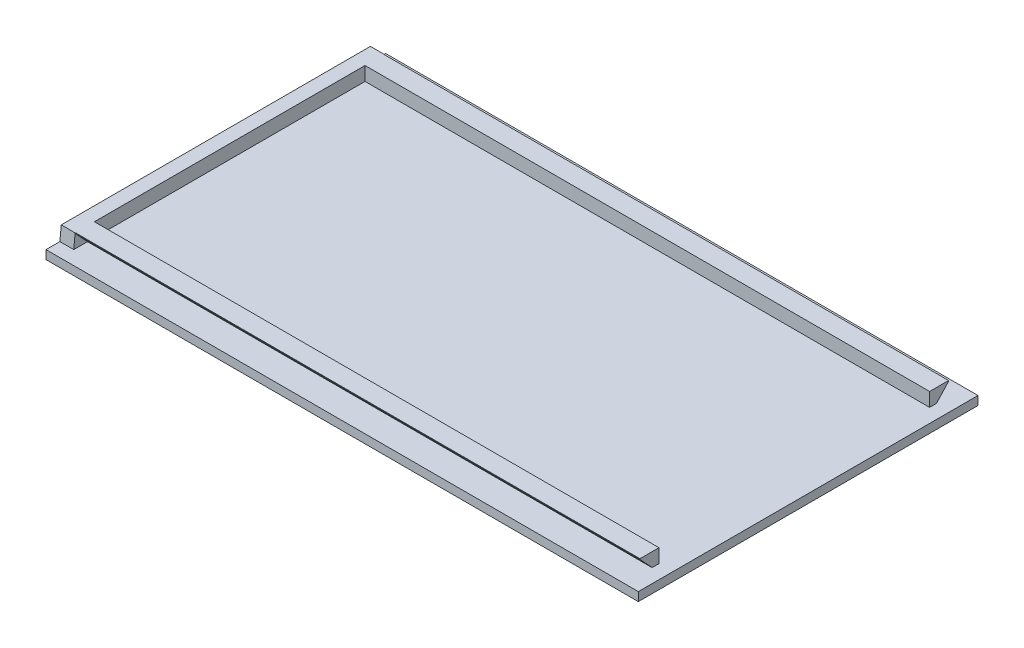
SolidWorks part; units mm, degrees
ref_plane "Plano frontal" through (0, 0, 0) normal (0, 0, 1) x (1, 0, 0)
ref_plane "Plano superior" through (0, 0, 0) normal (0, 1, 0) x (1, 0, 0)
ref_plane "Plano direito" through (0, 0, 0) normal (1, 0, 0) x (0, 0, -1)
sketch "Esboço1" plane through (0, 0, 0) normal (0, 1, 0) x (1, 0, 0)
  line L1 (0, 0) -> (85.8, 0)
  line L2 (0, 0) -> (0, 49.2)
  line L3 (0, 49.2) -> (85.8, 49.2)
  line L4 (85.8, 0) -> (85.8, 49.2)
  dimension "D1" = 85.8
  dimension "D2" = 49.2
extrude "Ressalto-extrusão1" add sketch "Esboço1" along normal blind 1.26
sketch "Esboço9" plane through (0, 0, 0) normal (-1, 0, 0) x (0, 0, 1)
  line L0 (-47.19, 1.26) -> (-46.9898, 3.26)
  line L1 (-49.2, 1.26) -> (0, 1.26) construction
  line L2 (-24.6, 1.26) -> (-24.6, 12.5039) construction
  line L3 (-46.9898, 3.26) -> (-2.2102, 3.26)
  line L4 (-2.01, 1.26) -> (-2.2102, 3.26)
  line L5 (-47.19, 1.26) -> (-2.01, 1.26)
  point P8 (-24.6, 3.26)
  dimension "D1" = 2
  dimension "D2" = 2.01
  dimension "D3" = 2.01
extrude "Ressalto-extrusão5" add sketch "Esboço9" against normal blind 2.01
sketch "Esboço11" plane through (85.8, 0, 0) normal (1, 0, 0) x (0, 0, -1)
  line L0 (44.2, 1.26) -> (45.2, 1.26)
  line L1 (0, 1.26) -> (49.2, 1.26) construction
  line L2 (45.2, 1.26) -> (46.9598, 3.1603)
  line L3 (46.9598, 3.1603) -> (46.9525, 3.26)
  line L4 (46.9525, 3.26) -> (44.2, 3.26)
  line L5 (44.2, 3.26) -> (44.2, 1.26)
  line L8 (24.6, 1.26) -> (24.6, 6.8528) construction
  line L9 (47.19, 1.26) -> (2.01, 1.26) construction
  line L10 (5, 3.26) -> (5, 1.26)
  line L11 (2.2475, 3.26) -> (5, 3.26)
  line L12 (2.2402, 3.1603) -> (2.2475, 3.26)
  line L13 (4, 1.26) -> (2.2402, 3.1603)
  line L14 (5, 1.26) -> (4, 1.26)
  dimension "D1" = 2
  dimension "D2" = 1
  dimension "D3" = 2.59
  dimension "D4" = 4
  dimension "D5" = 0.1
  dimension "D6" = 94.24
extrude "Ressalto-extrusão6" add sketch "Esboço11" against normal through all from offset 2.01 offset against normal yes
sketch "Esboço8" plane through (0, 0, 0) normal (0, -1, 0) x (1, 0, 0)
  line L9 (24.3584, -24.5768) -> (41.3246, -24.5768) construction
  arc A0 (22.0546, -24.5748) -> (24.5438, -35.0663) centre (24.3576, -29.5694) ccw
  arc A1 (24.5438, -14.0873) -> (22.0546, -24.5748) centre (24.367, -19.5845) ccw
  arc A2 (24.5438, -35.0663) -> (41.3246, -24.5768) centre (24.3632, -16.1099) ccw
  arc A3 (24.5438, -14.0873) -> (41.3246, -24.5768) centre (24.3632, -33.0437) cw
  arc A4 (24.5332, -14.5873) -> (24.0877, -24.5767) centre (24.367, -19.5845) ccw
  arc A5 (24.0877, -24.5767) -> (24.5328, -34.5663) centre (24.3576, -29.5694) ccw
  arc A6 (24.5328, -34.5663) -> (40.7638, -24.5768) centre (24.3632, -16.1099) ccw
  arc A7 (24.5332, -14.5873) -> (40.7638, -24.5768) centre (24.3632, -33.0437) cw
  dimension "D1" = 0.5
extrude "Corte-extrusão4" cut sketch "Esboço8" against normal blind 0.6
